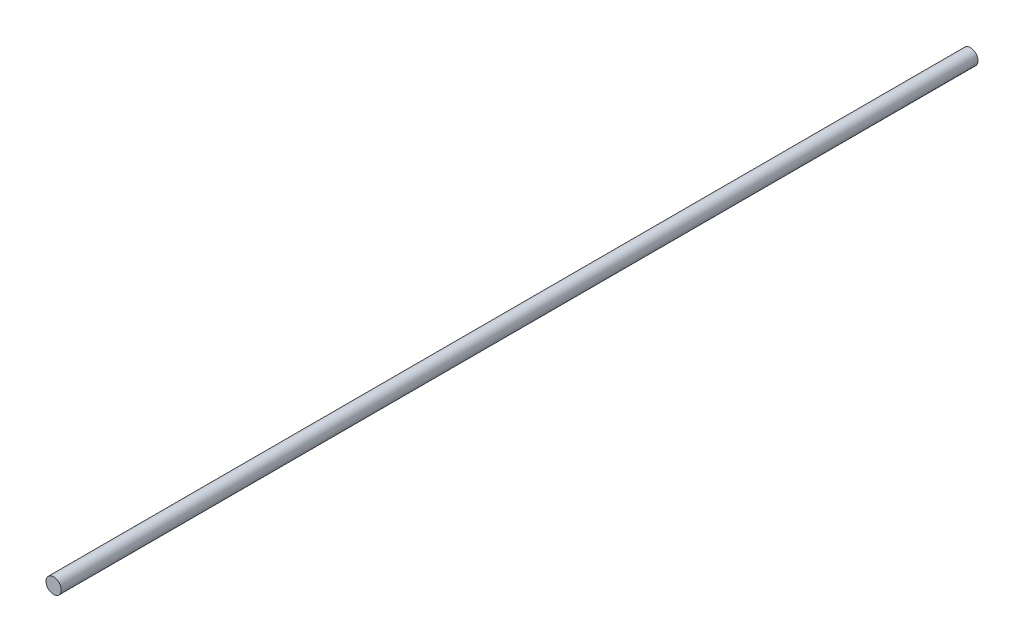
SolidWorks part; units mm, degrees
ref_plane "Front Plane" through (0, 0, 0) normal (0, 0, 1) x (1, 0, 0)
ref_plane "Top Plane" through (0, 0, 0) normal (0, 1, 0) x (1, 0, 0)
ref_plane "Right Plane" through (0, 0, 0) normal (1, 0, 0) x (0, 0, -1)
sketch "Sketch1" plane through (0, 0, 0) normal (0, 0, 1) x (1, 0, 0)
  circle A0 centre (0, 0) radius 1
  dimension "D1" = 2
extrude "Boss-Extrude1" add sketch "Sketch1" along normal blind 120
